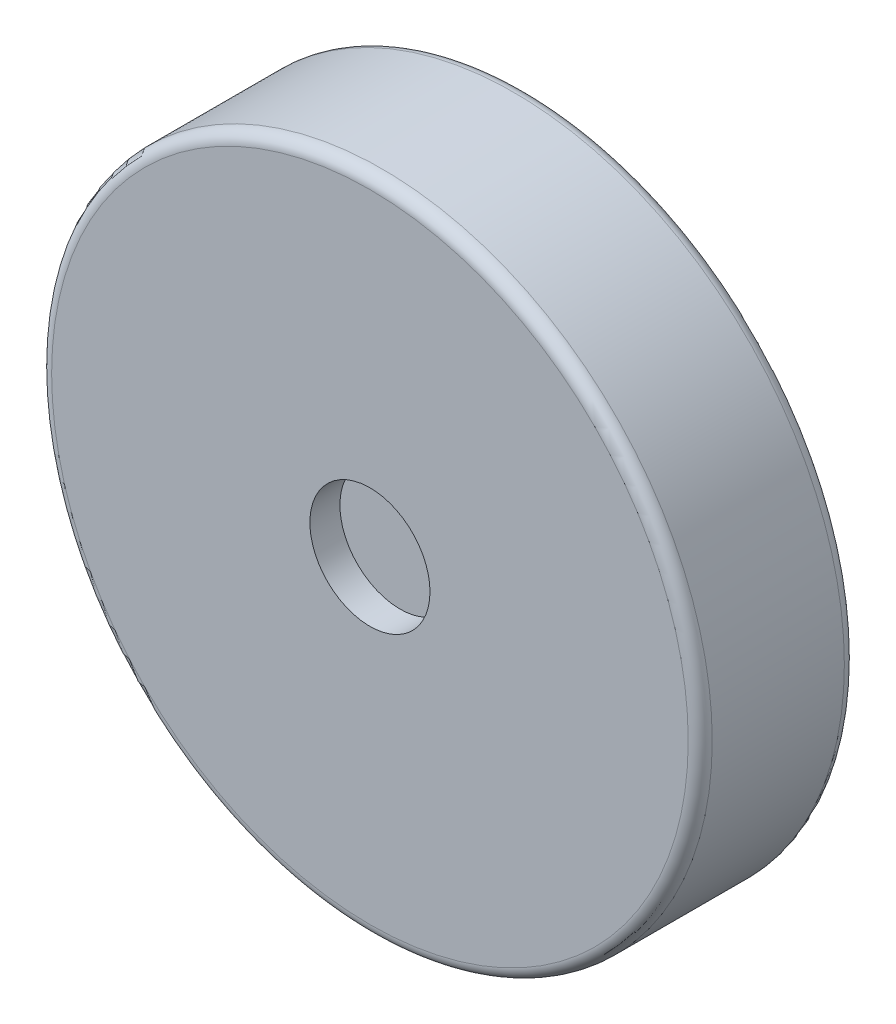
SolidWorks part; units mm, degrees
ref_plane "Front Plane" through (0, 0, 0) normal (0, 0, 1) x (1, 0, 0)
ref_plane "Top Plane" through (0, 0, 0) normal (0, 1, 0) x (1, 0, 0)
ref_plane "Right Plane" through (0, 0, 0) normal (1, 0, 0) x (0, 0, -1)
sketch "Sketch1" plane through (0, 0, 0) normal (0, 0, 1) x (1, 0, 0)
  line L0 (0, 0) -> (0, 21) construction
  circle A0 centre (0, 0) radius 55
  circle A1 centre (0, 0) radius 21 construction
  circle A2 centre (0, 21) radius 1.5
  circle A3 centre (14.8492, 14.8492) radius 1.5
  circle A4 centre (21, 0) radius 1.5
  circle A5 centre (14.8492, -14.8492) radius 1.5
  circle A6 centre (0, -21) radius 1.5
  circle A7 centre (-14.8492, -14.8492) radius 1.5
  circle A8 centre (-21, 0) radius 1.5
  circle A9 centre (-14.8492, 14.8492) radius 1.5
  dimension "D1" = 110
  dimension "D2" = 42
  dimension "D3" = 3
  dimension "D5" = 21
  dimension "D4" = 8
extrude "Boss-Extrude1" add sketch "Sketch1" along normal blind 26 contours A0
sketch "Sketch2" plane through (0, 0, 0) normal (0, 0, -1) x (-1, 0, 0)
  circle A1 centre (0, -21) radius 1.5
  circle A2 centre (0, -21) radius 1.5
  circle A3 centre (-14.8492, -14.8492) radius 1.5
  circle A4 centre (-14.8492, -14.8492) radius 1.5
  circle A5 centre (-21, 0) radius 1.5
  circle A6 centre (-21, 0) radius 1.5
  circle A7 centre (-14.8492, 14.8492) radius 1.5
  circle A8 centre (-14.8492, 14.8492) radius 1.5
  circle A9 centre (0, 21) radius 1.5
  circle A10 centre (0, 21) radius 1.5
  circle A13 centre (14.8492, 14.8492) radius 1.5
  circle A14 centre (14.8492, 14.8492) radius 1.5
  circle A15 centre (21, 0) radius 1.5
  circle A16 centre (21, 0) radius 1.5
  circle A17 centre (14.8492, -14.8492) radius 1.5
  circle A18 centre (14.8492, -14.8492) radius 1.5
  dimension "D1" = 0
  dimension "D2" = 0
  dimension "D3" = 0
  dimension "D4" = 0
  dimension "D5" = 0
  dimension "D7" = 0
  dimension "D8" = 0
  dimension "D9" = 0
extrude "Cut-Extrude1" cut sketch "Sketch2" against normal blind 3
sketch "Sketch3" plane through (0, 0, 26) normal (0, 0, 1) x (1, 0, 0)
  line L0 (0, 0) -> (0, 16.5) construction
  line L1 (0, 0) -> (-59.5603, 59.5603) construction
  line L2 (0, 0) -> (-87.189, 0) construction
  line L3 (0, 0) -> (-11.6673, 11.6673) construction
  line L4 (0, 0) -> (0, 22) construction
  circle A0 centre (0, 0) radius 26 construction
  circle A1 centre (0, 0) radius 22 construction
  circle A2 centre (0, 0) radius 16.5 construction
  circle A3 centre (0, 16.5) radius 2.55
  circle A4 centre (16.5, 0) radius 2.55
  circle A5 centre (0, -16.5) radius 2.55
  circle A6 centre (-16.5, 0) radius 2.55
  circle A7 centre (-11.6673, 11.6673) radius 2.05
  circle A8 centre (11.6673, 11.6673) radius 2.05
  circle A9 centre (11.6673, -11.6673) radius 2.05
  circle A10 centre (-11.6673, -11.6673) radius 2.05
  circle A11 centre (0, 22) radius 1.55
  circle A12 centre (0, 26) radius 1.55
  circle A13 centre (26, 0) radius 1.55
  circle A14 centre (22, 0) radius 1.55
  circle A15 centre (0, -26) radius 1.55
  circle A16 centre (0, -22) radius 1.55
  circle A17 centre (-26, 0) radius 1.55
  circle A18 centre (-22, 0) radius 1.55
  circle A19 centre (0, 0) radius 32.5
  dimension "D1" = 52
  dimension "D2" = 44
  dimension "D3" = 33
  dimension "D4" = 5.1
  dimension "D8" = 4.1
  dimension "D11" = 3.1
  dimension "D12" = 3.1
  dimension "D15" = 65
  dimension "D6" = 16.5
  dimension "D7" = 45
  dimension "D10" = 16.5
  dimension "D14" = 22
  dimension "D5" = 4
  dimension "D9" = 4
  dimension "D13" = 4
extrude "Boss-Extrude2" add sketch "Sketch3" along normal blind 8 contours A19
sketch "Sketch4" plane through (0, 0, 34) normal (0, 0, 1) x (1, 0, 0)
  circle A1 centre (-16.5, 0) radius 2.55
  circle A2 centre (-16.5, 0) radius 2.55
  circle A3 centre (0, -16.5) radius 2.55
  circle A4 centre (0, -16.5) radius 2.55
  circle A5 centre (16.5, 0) radius 2.55
  circle A6 centre (16.5, 0) radius 2.55
  circle A7 centre (0, 16.5) radius 2.55
  circle A8 centre (0, 16.5) radius 2.55
  circle A9 centre (0, 26) radius 1.55
  circle A10 centre (0, 26) radius 1.55
  circle A11 centre (0, 22) radius 1.55
  circle A12 centre (0, 22) radius 1.55
  circle A13 centre (-11.6673, -11.6673) radius 2.05
  circle A14 centre (-11.6673, -11.6673) radius 2.05
  circle A15 centre (11.6673, -11.6673) radius 2.05
  circle A16 centre (11.6673, -11.6673) radius 2.05
  circle A17 centre (11.6673, 11.6673) radius 2.05
  circle A18 centre (11.6673, 11.6673) radius 2.05
  circle A19 centre (-11.6673, 11.6673) radius 2.05
  circle A20 centre (-11.6673, 11.6673) radius 2.05
  circle A23 centre (-22, 0) radius 1.55
  circle A24 centre (-22, 0) radius 1.55
  circle A25 centre (-26, 0) radius 1.55
  circle A26 centre (-26, 0) radius 1.55
  circle A27 centre (0, -22) radius 1.55
  circle A28 centre (0, -22) radius 1.55
  circle A29 centre (0, -26) radius 1.55
  circle A30 centre (0, -26) radius 1.55
  circle A31 centre (22, 0) radius 1.55
  circle A32 centre (22, 0) radius 1.55
  circle A33 centre (26, 0) radius 1.55
  circle A34 centre (26, 0) radius 1.55
  dimension "D1" = 0
  dimension "D2" = 0
  dimension "D3" = 0
  dimension "D4" = 0
  dimension "D5" = 0
  dimension "D6" = 0
  dimension "D7" = 0
  dimension "D8" = 0
  dimension "D9" = 0
  dimension "D10" = 0
  dimension "D12" = 0
  dimension "D13" = 0
  dimension "D14" = 0
  dimension "D15" = 0
  dimension "D16" = 0
  dimension "D17" = 0
extrude "Cut-Extrude2" cut sketch "Sketch4" against normal blind 3
fillet "Fillet1" radius 2 2 edges at (55, 0, 26) (55, 0, 0)
sketch "Sketch5" plane through (0, 0, 0) normal (0, 0, -1) x (-1, 0, 0)
  line L0 (0, 53) -> (0, -53) construction
  circle A0 centre (0, 0) radius 53 construction
ref_plane "Plane1" through (0, 55, 0) normal (0, 1, 0) x (1, 0, 0)
sketch "Sketch6" plane through (0, 55, 0) normal (0, 1, 0) x (1, 0, 0)
  line L0 (0, -2) -> (0, -24) construction
  line L1 (55, -2) -> (-55, -2) construction
  line L2 (55, -24) -> (-55, -24) construction
sketch "Sketch7" plane through (0, 0, 0) normal (0, 1, 0) x (1, 0, 0)
  line L0 (0, 0) -> (0, -24) construction
  line L1 (55, -24) -> (-55, -24) construction
sketch "Sketch8" plane through (0, 0, 34) normal (0, 0, 1) x (1, 0, 0)
  line L0 (0, 0) -> (37.4767, 37.4767) construction
  line L1 (0, 0) -> (53, 0) construction
  circle A0 centre (0, 0) radius 53 construction
  dimension "D1" = 45
ref_plane "Plane2" through (0, 0, 26) normal (0, 0, 1) x (1, 0, 0)
sketch "Sketch9" plane through (0, 0, 26) normal (0, 0, 1) x (1, 0, 0)
  circle A0 centre (0, 0) radius 42.4159
  dimension "D1" = 84.8319
extrude "Cut-Extrude3" cut sketch "Sketch9" along normal through all
sketch "Sketch10" plane through (0, 0, 26) normal (0, 0, 1) x (1, 0, 0)
  line L0 (0, 53) -> (0, -53) construction
  circle A0 centre (0, 0) radius 10
  dimension "D1" = 20
extrude "Cut-Extrude4" cut sketch "Sketch10" against normal blind 5
sketch "Sketch11" plane through (0, 0, 0) normal (0, 0, -1) x (-1, 0, 0)
  circle A0 centre (0, 0) radius 21
